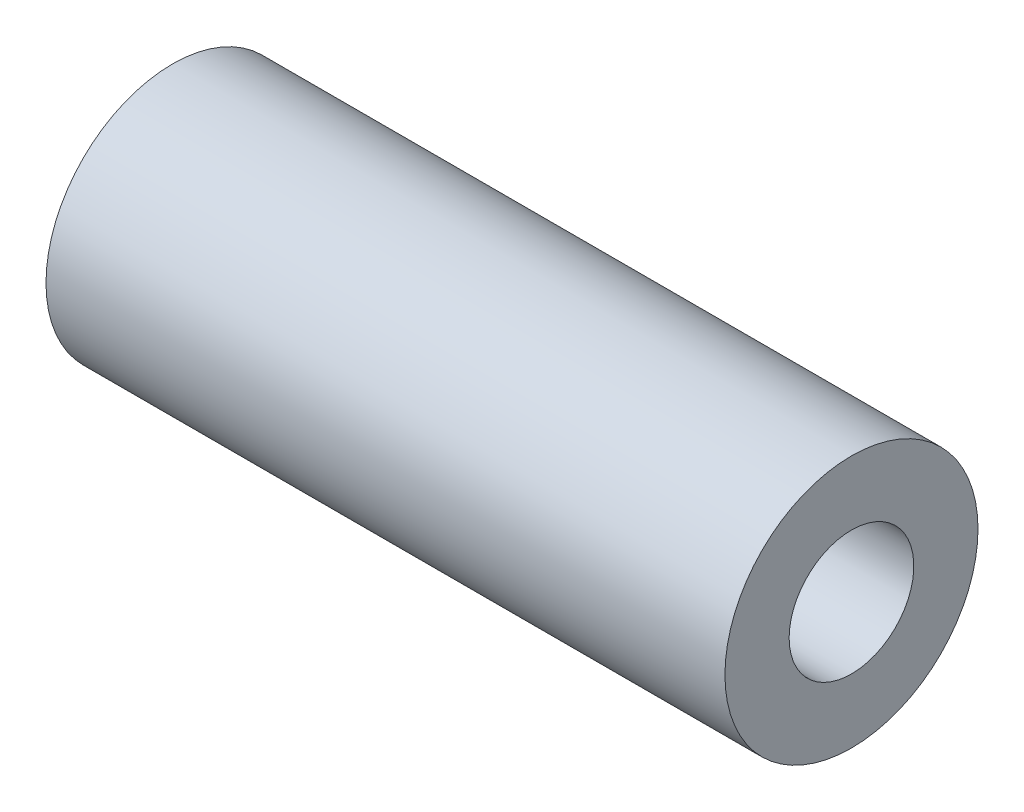
SolidWorks part; units mm, degrees
ref_plane "Front Plane" through (0, 0, 0) normal (0, 0, 1) x (1, 0, 0)
ref_plane "Top Plane" through (0, 0, 0) normal (0, 1, 0) x (1, 0, 0)
ref_plane "Right Plane" through (0, 0, 0) normal (1, 0, 0) x (0, 0, -1)
sketch "Sketch1" plane through (0, 0, 0) normal (0, 0, 1) x (1, 0, 0)
  line L0 (-61, 0) -> (-6, 0)
  line L1 (-61, 0) -> (-61, 5.2)
  line L2 (-61, 5.2) -> (-6, 5.2)
  line L3 (-6, 5.2) -> (-6, 14.95) construction
  line L4 (-6, 14.95) -> (-3, 14.95) construction
  line L5 (-3, 14.95) -> (0, 2.5) construction
  line L6 (0, 2.5) -> (0, 0) construction
  line L7 (-3, 14.95) -> (-3, 16.0231) construction
  line L8 (-62.9132, -5.05) -> (-20.3177, -5.05) construction
  line L9 (-6, 5.2) -> (-6, 0)
  dimension "D1" = 3
  dimension "D2" = 55
  dimension "D6" = 10.25
  dimension "D7" = 3
  dimension "D3" = 20
  dimension "D4" = 5.2005
  dimension "D8" = 6
  dimension "D5" = 5.05
revolve "Revolve1" add sketch "Sketch1" angle 360 about L8
equation "\"innerDiameter\"=25"
equation "\"chordThickness\"=9.5"
equation "\"chordLength\"=55"
equation "\"chrodDiameter\"=40"
equation "\"ArmLength\"=424"
equation "\"shockMountSpacing\"=30"
equation "\"shockMountHeight\"=55"
equation "\"shockMountAngle\"=40"
equation "\"BoltNominalDiameter\"=10"
equation "\"BushingInnerDiameter\"=10+0.1"
equation "\"ShockMountlength\"=35"
equation "\"D5@Sketch1\"=\"BushingInnerDiameter\"*0.5"
